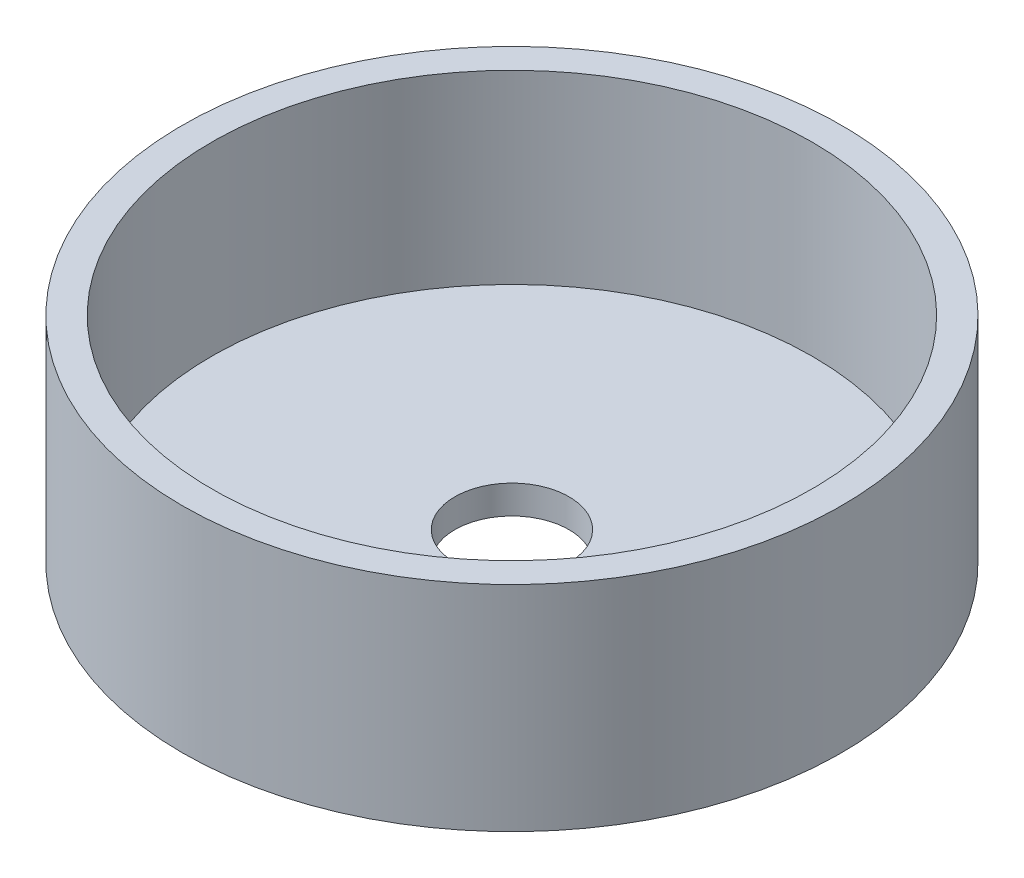
SolidWorks part; units mm, degrees
material "6061 合金"
ref_plane "前视基准面" through (0, 0, 0) normal (0, 0, 1) x (1, 0, 0)
ref_plane "上视基准面" through (0, 0, 0) normal (0, 1, 0) x (1, 0, 0)
ref_plane "右视基准面" through (0, 0, 0) normal (1, 0, 0) x (0, 0, -1)
sketch "草图1" plane through (0, 0, 0) normal (0, 1, 0) x (1, 0, 0)
  circle A0 centre (0, 0) radius 23.1
  dimension "D1" = 46.2
extrude "凸台-拉伸1" add sketch "草图1" along normal blind 2
sketch "草图2" plane through (0, 2, 0) normal (0, 1, 0) x (1, 0, 0)
  circle A0 centre (0, 0) radius 23.1
  circle A1 centre (0, 0) radius 21.05
  dimension "D1" = 42.1
  dimension "D2" = 46.2
extrude "凸台-拉伸2" add sketch "草图2" along normal blind 13
sketch "草图3" plane through (0, 2, 0) normal (0, 1, 0) x (1, 0, 0)
  circle A0 centre (0, 0) radius 4
  dimension "D1" = 8
extrude "切除-拉伸1" cut sketch "草图3" against normal through all
